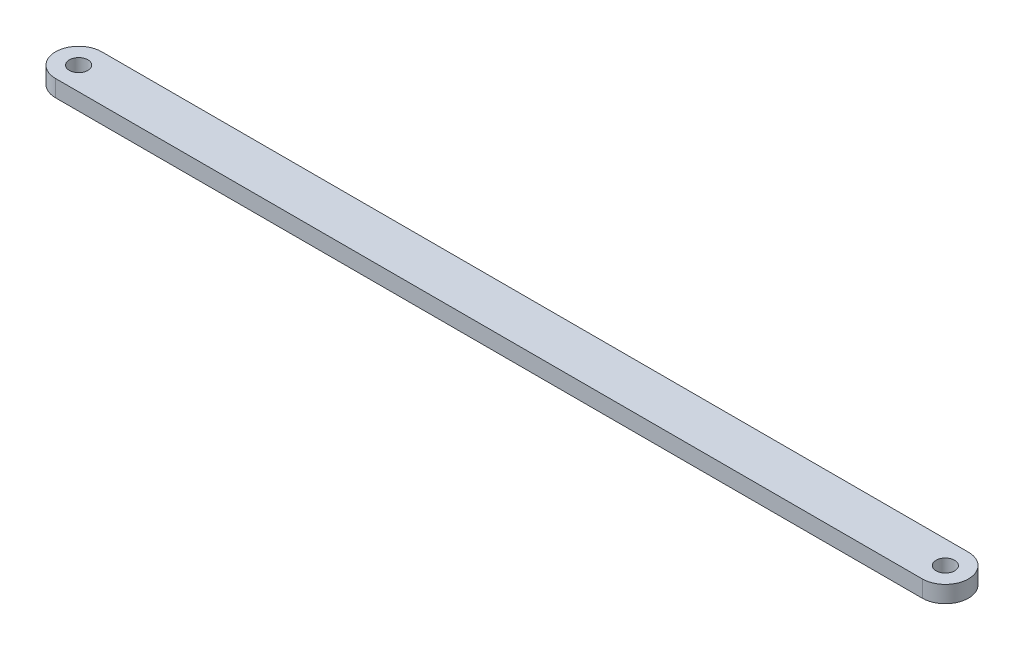
SolidWorks part; units mm, degrees
ref_plane "前视基准面" through (0, 0, 0) normal (0, 0, 1) x (1, 0, 0)
ref_plane "上视基准面" through (0, 0, 0) normal (0, 1, 0) x (1, 0, 0)
ref_plane "右视基准面" through (0, 0, 0) normal (1, 0, 0) x (0, 0, -1)
sketch "Sketch1" plane through (0, 0, 0) normal (0, 1, 0) x (1, 0, 0)
  line L0 (0, 0) -> (150, 0) construction
  line L1 (0, 4) -> (150, 4)
  line L2 (0, -4) -> (150, -4)
  arc A0 (0, 4) -> (0, -4) centre (0, 0) ccw
  arc A1 (150, -4) -> (150, 4) centre (150, 0) ccw
  circle A2 centre (0, 0) radius 1.6
  circle A3 centre (150, 0) radius 1.6
  point P3 (75, 0)
  dimension "D2" = 4
  dimension "D3" = 3.2
  dimension "D4" = 3.2
  dimension "D1" = 150
extrude "Boss-Extrude1" add sketch "Sketch1" along normal blind 2.9
